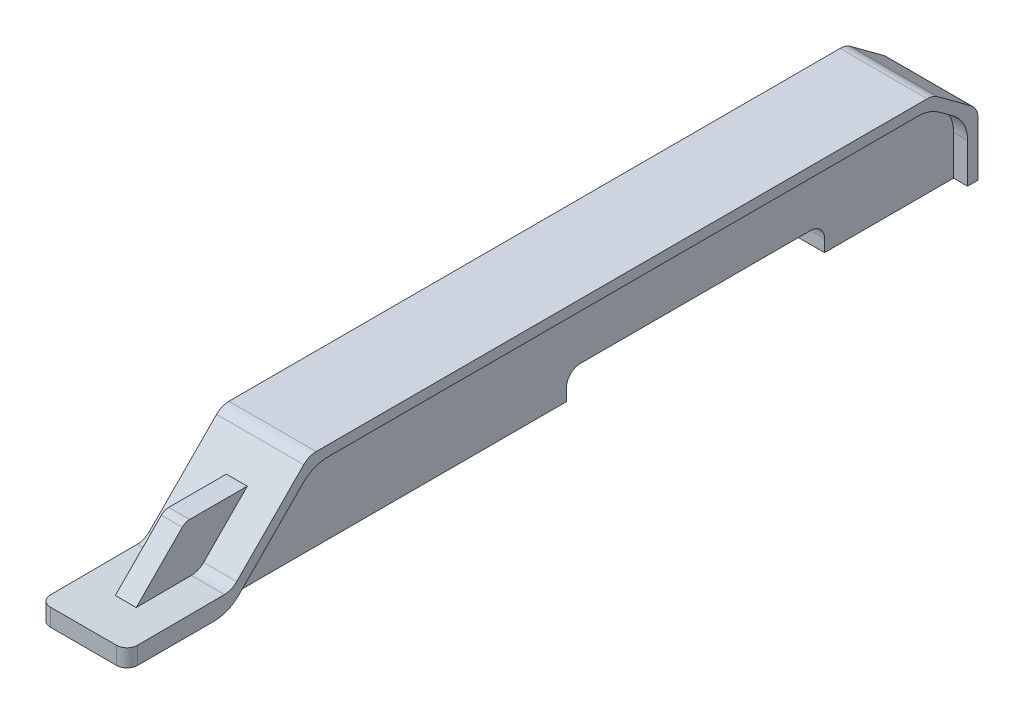
SolidWorks part; units mm, degrees
ref_plane "Front Plane" through (0, 0, 0) normal (0, 0, 1) x (1, 0, 0)
ref_plane "Top Plane" through (0, 0, 0) normal (0, 1, 0) x (1, 0, 0)
ref_plane "Right Plane" through (0, 0, 0) normal (1, 0, 0) x (0, 0, -1)
sketch "Sketch1" plane through (0, 0, 0) normal (1, 0, 0) x (0, 0, -1)
  line L0 (0, 0) -> (-130, 0)
  line L1 (0, 0) -> (74, 0) construction
  line L2 (0, 0) -> (0, 7.5)
  line L3 (0, 7.5) -> (74, 7.5)
  line L4 (74, 7.5) -> (74, 0)
  line L5 (74, 0) -> (114, 0)
  line L6 (-130, 0) -> (-130, 5)
  line L7 (-130, 5) -> (-100.0004, 5.1483)
  line L8 (-100.0004, 5.1483) -> (-77.8685, 27.5)
  line L9 (114, 0) -> (114, 18)
  line L10 (114, 18) -> (101.0882, 27.5)
  line L11 (101.0882, 27.5) -> (-77.8685, 27.5)
  point P12 (-37.7081, 45.4937)
  dimension "D1" = 130
  dimension "D2" = 74
  dimension "D3" = 7.5
  dimension "D4" = 40
  dimension "D5" = 30
  dimension "D6" = 5
  dimension "D7" = 135
  dimension "D8" = 20
  dimension "D9" = 18
extrude "Boss-Extrude1" add sketch "Sketch1" along normal blind 25
sketch "Sketch4" plane through (25, 0, 0) normal (1, 0, 0) x (0, 0, -1)
  line L11 (-130, 0) -> (0, 0) construction
  line L12 (-130, 0) -> (0, 0) construction
  line L13 (-100.8762, 0) -> (0, 0)
  line L14 (0, 0) -> (111, 0)
  line L15 (74, 0) -> (114, 0) construction
  line L16 (111, 0) -> (111, 3)
  line L22 (-3, 3) -> (-3, 10.5)
  line L23 (-3, 10.5) -> (77, 10.5)
  line L24 (77, 10.5) -> (77, 3)
  line L25 (77, 3) -> (111, 3)
  line L26 (111, 3) -> (111, 16.4828)
  line L27 (111, 16.4828) -> (100.1035, 24.5)
  line L28 (100.1035, 24.5) -> (-76.6172, 24.5)
  line L29 (-76.6172, 24.5) -> (-97.9057, 3)
  line L30 (-97.9057, 3) -> (-3, 3)
  line L35 (111, 3) -> (111, 16.4828)
  line L36 (111, 16.4828) -> (100.1035, 24.5)
  line L37 (100.1035, 24.5) -> (-76.6172, 24.5)
  line L38 (-76.6172, 24.5) -> (-100.8762, 0)
  dimension "D1" = 3
extrude "Cut-Extrude1" cut sketch "Sketch4" against normal blind 4
ref_plane "Plane1" through (12.5, 0, 0) normal (1, 0, 0) x (0, 0, -1)
mirror "Mirror2" about plane through (12.5, 0, 0) normal (1, 0, 0) of "Cut-Extrude1"
fillet "Fillet1" radius 4 2 edges at (12.5, 7.5, -74) (12.5, 7.5, 0)
fillet "Fillet2" radius 10 8 edges at (23, 16.4828, -111) (23, 24.5, -100.1035) (2, 16.4828, -111) (2, 24.5, -100.1035) (2, 24.5, 76.6172) (23, 24.5, 76.6172) (2, 0, 100.8762) (23, 0, 100.8762)
fillet "Fillet3" radius 5 4 edges at (12.5, 18, -114) (12.5, 27.5, -101.0882) (12.5, 27.5, 77.8685) (12.5, 5.1483, 100.0004)
fillet "Fillet4" radius 3 2 edges at (0, 2.5, 130) (25, 2.5, 130)
sketch "Sketch5" plane through (12.5, 0, 0) normal (1, 0, 0) x (0, 0, -1)
  line L0 (-117.866, 5.06) -> (-103.7939, 19.2718)
  line L1 (-102.0714, 5.138) -> (-127, 5.0148) construction
  line L2 (-79.3359, 26.018) -> (-98.5432, 6.62) construction
  line L3 (-103.7939, 19.2718) -> (-72.6053, 19.2718)
  line L4 (-117.866, 5.06) -> (-95.866, 5.06)
  line L5 (-79.552, 21.536) -> (-97.9414, 2.964) construction
  line L6 (-72.6053, 19.2718) -> (-95.866, 5.06)
  dimension "D1" = 22
  dimension "D2" = 20
extrude "Boss-Extrude2" add sketch "Sketch5" along normal blind 3 and the other way blind 3
fillet "Fillet5" radius 3 1 edges at (12.5, 19.2718, 103.7939)
